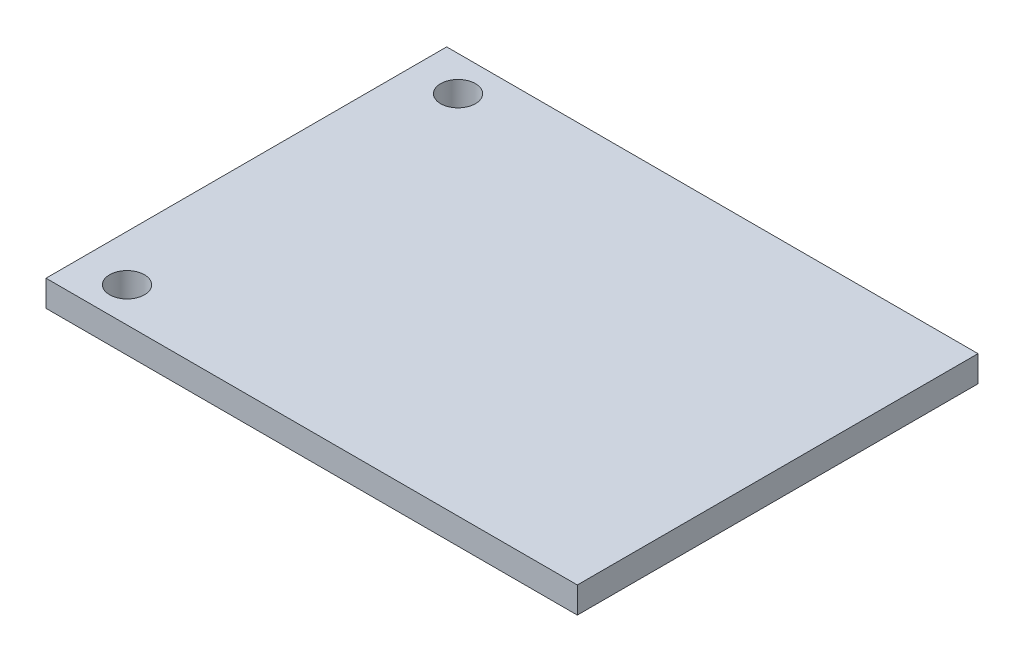
SolidWorks part; units mm, degrees
ref_plane "Front Plane" through (0, 0, 0) normal (0, 0, 1) x (1, 0, 0)
ref_plane "Top Plane" through (0, 0, 0) normal (0, 1, 0) x (1, 0, 0)
ref_plane "Right Plane" through (0, 0, 0) normal (1, 0, 0) x (0, 0, -1)
sketch "Sketch1" plane through (0, 0, 0) normal (0, 1, 0) x (1, 0, 0)
  line L1 (-15.25, 11.5) -> (15.25, 11.5)
  line L2 (-15.25, 11.5) -> (-15.25, -11.5)
  line L3 (-15.25, -11.5) -> (15.25, -11.5)
  line L4 (15.25, 11.5) -> (15.25, -11.5)
  line L5 (-15.25, 11.5) -> (15.25, -11.5) construction
  line L6 (-15.25, -11.5) -> (15.25, 11.5) construction
  line L7 (-12.5978, 9.5) -> (12.5978, 9.5)
  line L8 (-12.5978, 9.5) -> (-12.5978, -9.5)
  line L9 (-12.5978, -9.5) -> (12.5978, -9.5)
  line L10 (12.5978, 9.5) -> (12.5978, -9.5)
  line L11 (-12.5978, 9.5) -> (12.5978, -9.5) construction
  line L12 (-12.5978, -9.5) -> (12.5978, 9.5) construction
  circle A0 centre (-12.5978, 9.5) radius 1
  circle A1 centre (-12.5978, -9.5) radius 1
  point P0 (0, 0)
  point P6 (0, 0)
  dimension "D4" = 2
  dimension "D1" = 30.5
  dimension "D2" = 23
  dimension "D3" = 19
extrude "Boss-Extrude1" add sketch "Sketch1" along normal blind 1.5 contours A1 L9 L10 L7 A0 L8 | L4 L1 L2 L3 A1 L8 A0 L7 L10 L9
